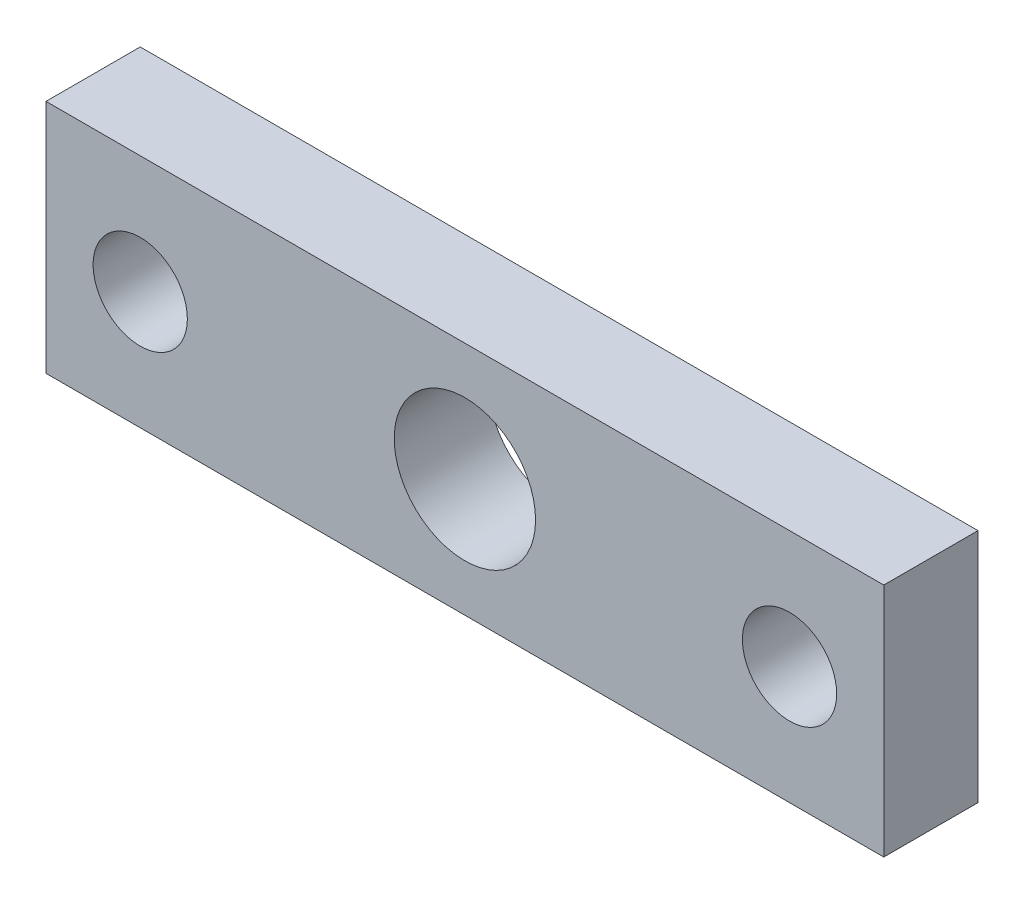
SolidWorks part; units mm, degrees
ref_plane "Front Plane" through (0, 0, 0) normal (0, 0, 1) x (1, 0, 0)
ref_plane "Top Plane" through (0, 0, 0) normal (0, 1, 0) x (1, 0, 0)
ref_plane "Right Plane" through (0, 0, 0) normal (1, 0, 0) x (0, 0, -1)
sketch "Sketch1" plane through (0, 0, 0) normal (0, 0, 1) x (1, 0, 0)
  line L1 (0, 0) -> (88.9, 0)
  line L2 (0, 0) -> (0, 25)
  line L3 (0, 25) -> (88.9, 25)
  line L4 (88.9, 0) -> (88.9, 25)
  dimension "D1" = 88.9
  dimension "D2" = 25
extrude "Boss-Extrude1" add sketch "Sketch1" along normal blind 10
sketch "Sketch2" plane through (0, 0, 10) normal (0, 0, 1) x (1, 0, 0)
  line L0 (0, 12.5) -> (88.9, 12.5) construction
  line L1 (0, 25) -> (0, 0) construction
  line L2 (88.9, 0) -> (88.9, 25) construction
  circle A0 centre (10, 12.5) radius 5
  circle A1 centre (78.9, 12.5) radius 5
  circle A2 centre (44.45, 12.5) radius 7.5
  dimension "D1" = 10
  dimension "D2" = 10
  dimension "D3" = 10
  dimension "D4" = 15
extrude "Cut-Extrude1" cut sketch "Sketch2" against normal through all
